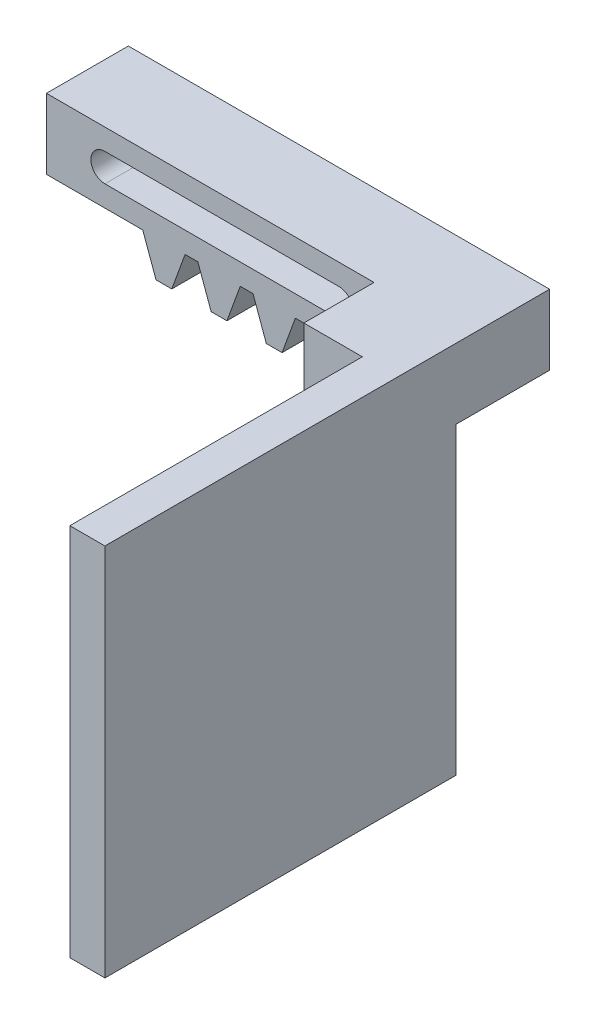
SolidWorks part; units mm, degrees
ref_plane "Front Plane" through (0, 0, 0) normal (0, 0, 1) x (1, 0, 0)
ref_plane "Top Plane" through (0, 0, 0) normal (0, 1, 0) x (1, 0, 0)
ref_plane "Right Plane" through (0, 0, 0) normal (1, 0, 0) x (0, 0, -1)
sketch "Sketch1" plane through (0, 0, 0) normal (0, 0, 1) x (1, 0, 0)
  line L0 (-23, 19.975) -> (13, 19.975)
  line L1 (13, 19.975) -> (13, 13.975)
  line L2 (13, 13.975) -> (7.701, 13.975)
  line L3 (7.701, 13.975) -> (6.5636, 10.85)
  line L4 (6.5636, 10.85) -> (5.2174, 10.85)
  line L5 (5.2174, 10.85) -> (4.0799, 13.975)
  line L6 (4.0799, 13.975) -> (2.9886, 13.975)
  line L7 (2.9886, 13.975) -> (1.8512, 10.85)
  line L8 (1.8512, 10.85) -> (0.505, 10.85)
  line L9 (0.505, 10.85) -> (-0.6324, 13.975)
  line L10 (-0.6324, 13.975) -> (-1.7238, 13.975)
  line L11 (-1.7238, 13.975) -> (-2.8612, 10.85)
  line L12 (-2.8612, 10.85) -> (-4.2074, 10.85)
  line L13 (-4.2074, 10.85) -> (-5.3448, 13.975)
  line L14 (-5.3448, 13.975) -> (-6.4361, 13.975)
  line L15 (-6.4361, 13.975) -> (-7.5735, 10.85)
  line L16 (-7.5735, 10.85) -> (-8.9198, 10.85)
  line L17 (-8.9198, 10.85) -> (-10.0572, 13.975)
  line L18 (-10.0572, 13.975) -> (-11.1485, 13.975)
  line L19 (-11.1485, 13.975) -> (-12.2859, 10.85)
  line L20 (-12.2859, 10.85) -> (-13.6322, 10.85)
  line L21 (-13.6322, 10.85) -> (-14.7696, 13.975)
  line L22 (-14.7696, 13.975) -> (-23, 13.975)
  line L23 (-23, 13.975) -> (-23, 19.975)
extrude "Boss-Extrude1" add sketch "Sketch1" along normal blind 7 from offset 13.5
sketch "Sketch2" plane through (0, 0, 0) normal (0, 0, 1) x (1, 0, 0)
  line L0 (5, 13.975) -> (13, 13.975)
  line L1 (13, 13.975) -> (13, 19.975)
  line L2 (13, 19.975) -> (5, 19.975)
  line L3 (5, 19.975) -> (5, 13.975)
extrude "Boss-Extrude2" add sketch "Sketch2" along normal blind 6 from offset 20.5
sketch "Sketch3" plane through (0, 0, 0) normal (0, 0, 1) x (1, 0, 0)
  line L0 (10, -12) -> (13, -12)
  line L1 (13, -12) -> (13, 19.975)
  line L2 (13, 19.975) -> (10, 19.975)
  line L3 (10, 19.975) -> (10, -12)
extrude "Boss-Extrude3" add sketch "Sketch3" along normal blind 30 from offset 21.5
sketch "Sketch4" plane through (0, 0, 0) normal (0, 0, 1) x (1, 0, 0)
  line L0 (-18, 15.775) -> (2, 15.775)
  line L1 (2, 15.775) -> (2, 18.175)
  line L2 (2, 18.175) -> (-18, 18.175)
  line L3 (-18, 18.175) -> (-18, 15.775)
extrude "Cut-Extrude1" cut sketch "Sketch4" against normal through all and the other way through all
sketch "Sketch5" plane through (0, 0, 0) normal (0, 0, 1) x (1, 0, 0)
  circle A0 centre (-18, 16.975) radius 1.2
  circle A1 centre (2, 16.975) radius 1.2
extrude "Cut-Extrude2" cut sketch "Sketch5" against normal through all and the other way through all
